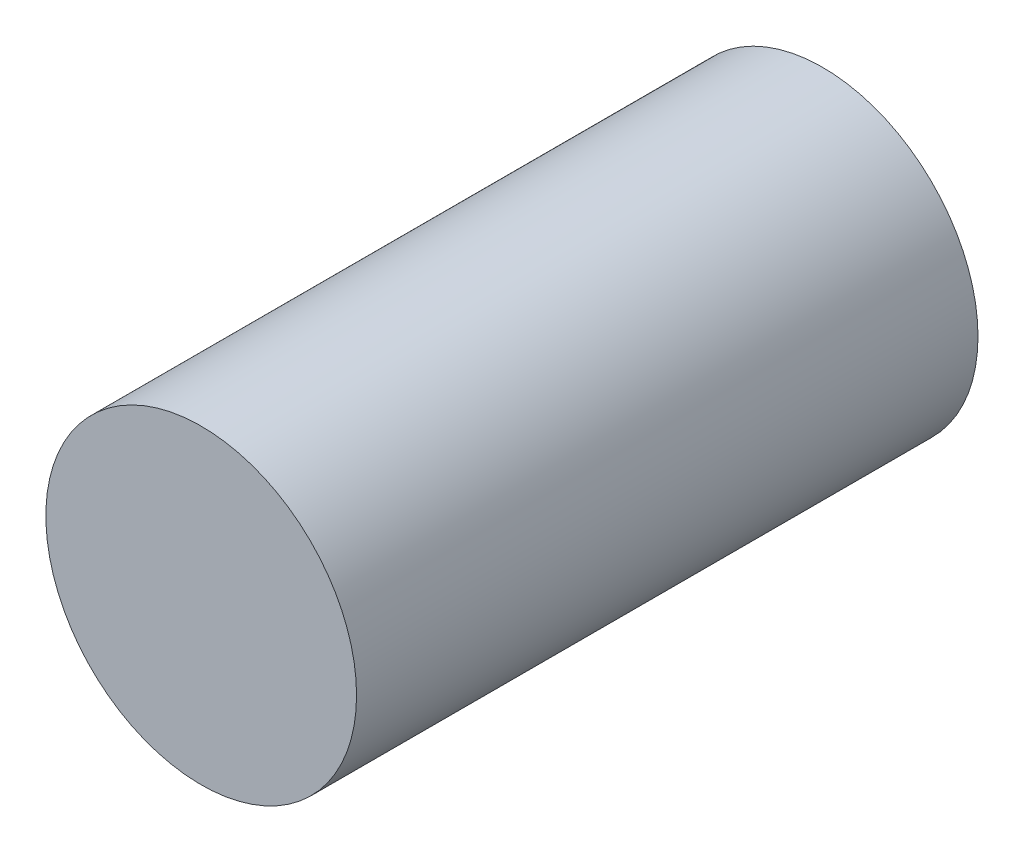
SolidWorks part; units mm, degrees
ref_plane "Front Plane" through (0, 0, 0) normal (0, 0, 1) x (1, 0, 0)
ref_plane "Top Plane" through (0, 0, 0) normal (0, 1, 0) x (1, 0, 0)
ref_plane "Right Plane" through (0, 0, 0) normal (1, 0, 0) x (0, 0, -1)
sketch "Sketch1" plane through (0, 0, 0) normal (0, 0, 1) x (1, 0, 0)
  circle A0 centre (0, 0) radius 50
  dimension "D1" = 100
extrude "Boss-Extrude1" add sketch "Sketch1" along normal blind 200
